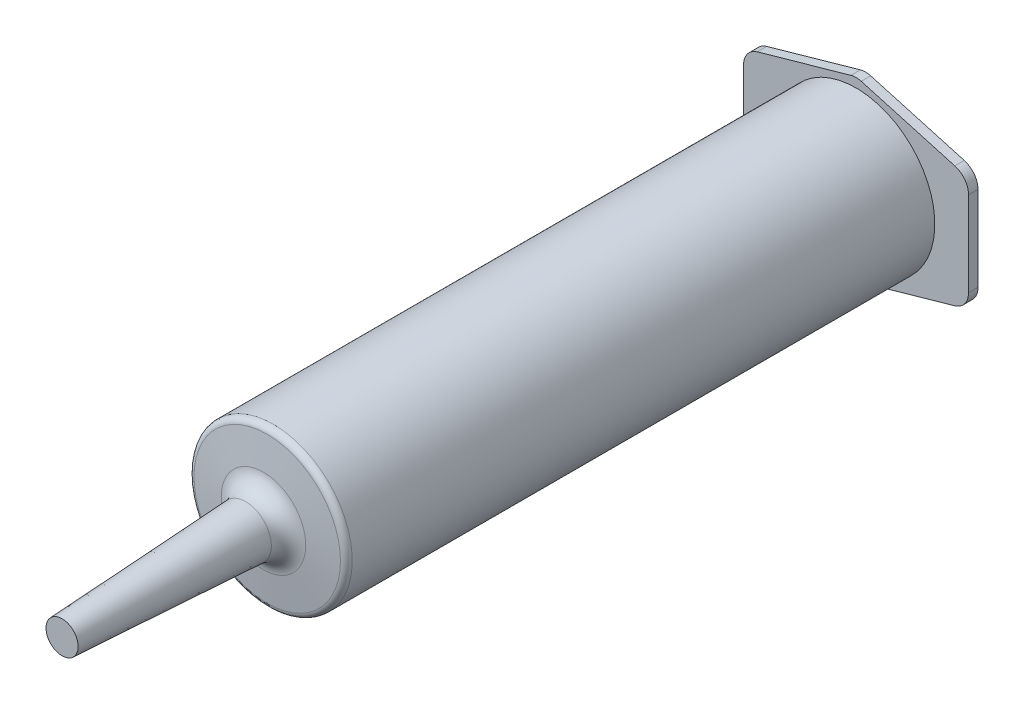
SolidWorks part; units mm, degrees
material "ABS PC"
ref_plane "Front Plane" through (0, 0, 0) normal (0, 0, 1) x (1, 0, 0)
ref_plane "Top Plane" through (0, 0, 0) normal (0, 1, 0) x (1, 0, 0)
ref_plane "Right Plane" through (0, 0, 0) normal (1, 0, 0) x (0, 0, -1)
sketch "Sketch1" plane through (0, 0, 0) normal (0, 1, 0) x (1, 0, 0)
  line L0 (16.0383, 117.8152) -> (16.0383, -2.6316)
  line L1 (16.0383, -2.6316) -> (5.4973, -3.9016)
  line L2 (5.4973, -3.9016) -> (3.4018, -44.1098)
  line L3 (3.4018, -44.1098) -> (0.1633, -44.1098)
  line L4 (0.1633, -44.1098) -> (0.1633, 117.8152)
  line L5 (0.1633, 117.8152) -> (16.0383, 117.8152)
  point P2 (1.7825, -44.1098)
  dimension "D1" = 15.875
  dimension "D2" = 3.2385
  dimension "D3" = 5.334
  dimension "D4" = 120.4468
  dimension "D5" = 121.7168
  dimension "D6" = 161.925
revolve "Revolve1" add sketch "Sketch1" angle 360 about L4
fillet "Fillet1" radius 3.81 1 edges at (5.4973, 0, 3.9016)
shell "Shell1" thickness 1.905
sketch "Sketch2" plane through (0, 0, -117.8152) normal (0, 0, -1) x (-1, 0, 0)
  line L2 (-0.1633, -17.8435) -> (22.5062, -11.43)
  line L3 (22.5062, -11.43) -> (22.5062, 11.43)
  line L4 (-1046.0353, 0) -> (48953.9647, 0) construction
  line L5 (-0.1633, 17.8435) -> (22.5062, 11.43)
  line L7 (-0.1633, 15.875) -> (-0.1633, -15.875)
  line L8 (-16.0383, 0) -> (15.7117, 0)
  line L9 (-0.1633, 17.8435) -> (-0.1633, -17.8435) construction
  line L10 (-0.1633, -17.8435) -> (-22.8328, -11.43)
  line L11 (-22.8328, -11.43) -> (-22.8328, 11.43)
  line L12 (-0.1633, 17.8435) -> (-22.8328, 11.43)
  circle A0 centre (-0.1633, 0) radius 15.875 construction
  circle M12 centre (-0.1633, 0) radius 15.875
  dimension "D1" = 22.6695
  dimension "D2" = 35.687
  dimension "D3" = 22.86
extrude "Boss-Extrude1" add sketch "Sketch2" against normal blind 1.905 contours L5 L12 L11 L10 L2 L3 M12
fillet "Fillet2" radius 3.81 6 edges at (0.1633, 17.8435, -116.8627) (22.8328, 11.43, -116.8627) (22.8328, -11.43, -116.8627) (0.1633, -17.8435, -116.8627) (-22.5062, 11.43, -116.8627) (-22.5062, -11.43, -116.8627)
fillet "Fillet3" radius 1.27 1 edges at (16.0383, 0, 2.6316)
